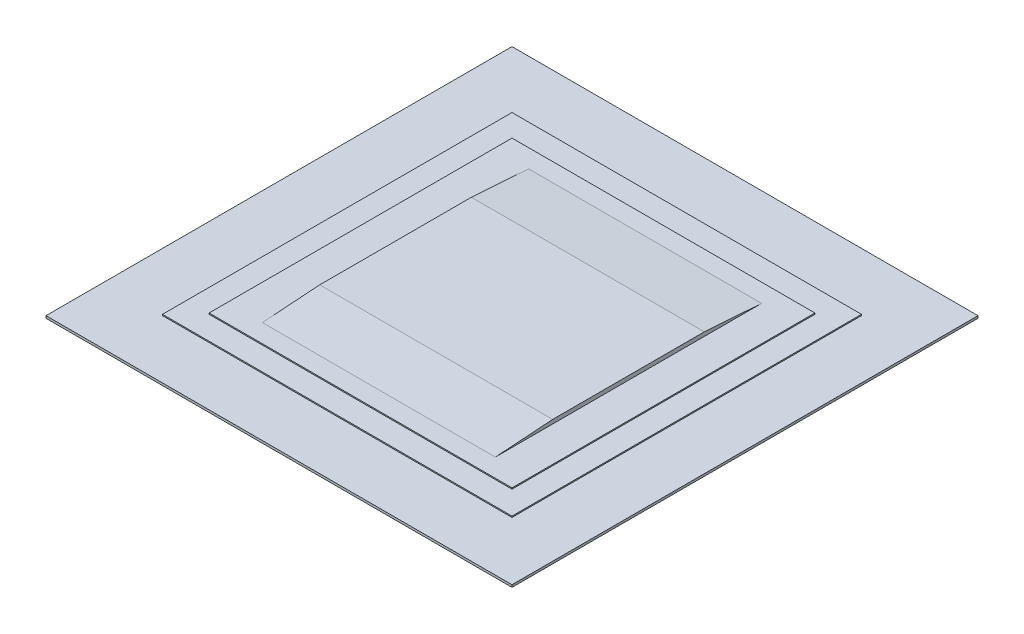
SolidWorks part; units mm, degrees
ref_plane "Plan de face" through (0, 0, 0) normal (0, 0, 1) x (1, 0, 0)
ref_plane "Plan de dessus" through (0, 0, 0) normal (0, 1, 0) x (1, 0, 0)
ref_plane "Plan de droite" through (0, 0, 0) normal (1, 0, 0) x (0, 0, -1)
sketch "Esquisse1" plane through (0, 0, 0) normal (0, 1, 0) x (1, 0, 0)
  line L1 (-1000, 1000) -> (1000, 1000)
  line L2 (-1000, 1000) -> (-1000, -1000)
  line L3 (-1000, -1000) -> (1000, -1000)
  line L4 (1000, 1000) -> (1000, -1000)
  line L5 (-1000, 1000) -> (1000, -1000) construction
  line L6 (-1000, -1000) -> (1000, 1000) construction
  point P0 (0, 0)
  dimension "D1" = 2000
  dimension "D2" = 2000
extrude "Boss.-Extru.1" add sketch "Esquisse1" along normal blind 10
sketch "Esquisse3" plane through (0, 10, 0) normal (0, 1, 0) x (1, 0, 0)
  line L1 (-750, 750) -> (750, 750)
  line L2 (-750, 750) -> (-750, -750)
  line L3 (-750, -750) -> (750, -750)
  line L4 (750, 750) -> (750, -750)
  line L5 (-750, 750) -> (750, -750) construction
  line L6 (-750, -750) -> (750, 750) construction
  point P0 (0, 0)
  dimension "D1" = 1500
  dimension "D2" = 1500
extrude "Boss.-Extru.2" add sketch "Esquisse3" along normal blind 5
sketch "Esquisse4" plane through (0, 15, 0) normal (0, 1, 0) x (1, 0, 0)
  line L1 (-650, 650) -> (650, 650)
  line L2 (-650, 650) -> (-650, -650)
  line L3 (-650, -650) -> (650, -650)
  line L4 (650, 650) -> (650, -650)
  line L5 (-650, 650) -> (650, -650) construction
  line L6 (-650, -650) -> (650, 650) construction
  point P0 (0, 0)
  dimension "D1" = 1300
  dimension "D2" = 1300
extrude "Boss.-Extru.3" add sketch "Esquisse4" along normal blind 5
sketch "Esquisse8" plane through (0, 0, 0) normal (1, 0, 0) x (0, 0, -1)
  line L0 (0, 295.9343) -> (0, -252.4608) construction
  line L2 (325.451, 37.1964) -> (-325.451, 37.1964)
  line L3 (-325.451, 37.1964) -> (-571.3714, 20)
  line L4 (-650, 20) -> (650, 20) construction
  line L5 (325.451, 37.1964) -> (571.3714, 20)
  line L6 (-571.3714, 20) -> (571.3714, 20)
  point P5 (0, 37.1964)
  dimension "D1" = 4
extrude "Boss.-Extru.5" add sketch "Esquisse8" along normal mid plane 1000
